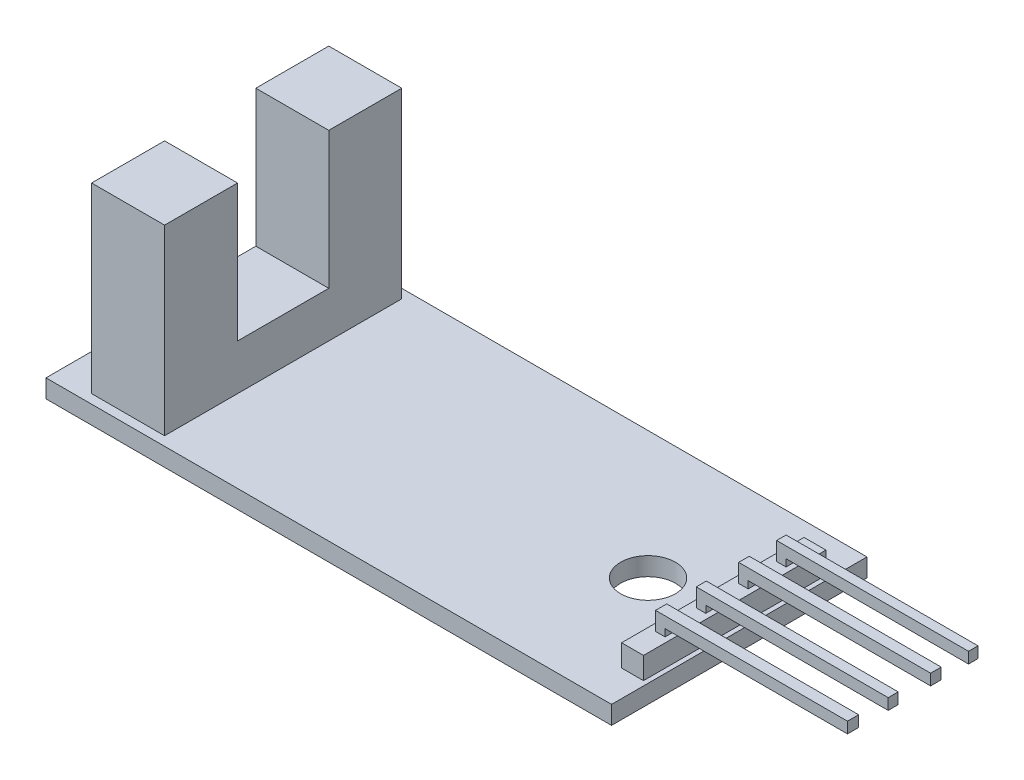
SolidWorks part; units mm, degrees
ref_plane "Front Plane" through (0, 0, 0) normal (0, 0, 1) x (1, 0, 0)
ref_plane "Top Plane" through (0, 0, 0) normal (0, 1, 0) x (1, 0, 0)
ref_plane "Right Plane" through (0, 0, 0) normal (1, 0, 0) x (0, 0, -1)
sketch "Sketch1" plane through (0, 0, 0) normal (0, 1, 0) x (1, 0, 0)
  line L1 (0, 0) -> (31, 0)
  line L2 (0, 0) -> (0, -14)
  line L3 (0, -14) -> (31, -14)
  line L4 (31, 0) -> (31, -14)
  dimension "D1" = 31
  dimension "D2" = 14
extrude "Boss-Extrude1" add sketch "Sketch1" along normal blind 1
sketch "Sketch2" plane through (0, 1, 0) normal (0, 1, 0) x (1, 0, 0)
  line L0 (0, -14) -> (31, -14) construction
  line L1 (2, -13.5) -> (6, -13.5)
  line L2 (2, -13.5) -> (2, -9.5)
  line L3 (2, -9.5) -> (6, -9.5)
  line L4 (6, -13.5) -> (6, -9.5)
  line L5 (2, -4.5) -> (6, -4.5)
  line L6 (2, -4.5) -> (2, -0.5)
  line L7 (2, -0.5) -> (6, -0.5)
  line L8 (6, -4.5) -> (6, -0.5)
  line L9 (0, 0) -> (0, -14) construction
  dimension "D1" = 5
  dimension "D2" = 4
  dimension "D3" = 4
  dimension "D4" = 0.5
  dimension "D5" = 4
  dimension "D6" = 4
  dimension "D7" = 2
  dimension "D8" = 2
extrude "Boss-Extrude2" add sketch "Sketch2" along normal blind 10
sketch "Sketch3" plane through (0, 1, 0) normal (0, 1, 0) x (1, 0, 0)
  line L0 (31, -14) -> (31, 0) construction
  circle A0 centre (26, -7) radius 1.5
  dimension "D1" = 3
  dimension "D2" = 5
extrude "Cut-Extrude1" cut sketch "Sketch3" against normal through all
sketch "Sketch4" plane through (0, 1, 0) normal (0, 1, 0) x (1, 0, 0)
  line L1 (2, -4.5) -> (6, -4.5)
  line L2 (2, -4.5) -> (2, -9.5)
  line L3 (2, -9.5) -> (6, -9.5)
  line L4 (6, -4.5) -> (6, -9.5)
extrude "Boss-Extrude3" add sketch "Sketch4" along normal blind 2.5
sketch "草图1" plane through (0, 1, 0) normal (0, 1, 0) x (1, 0, 0)
  line L0 (31, 0) -> (0, 0) construction
  line L1 (30.7509, -2) -> (29.5509, -2)
  line L2 (30.7509, -2) -> (30.7509, -12)
  line L3 (30.7509, -12) -> (29.5509, -12)
  line L4 (29.5509, -2) -> (29.5509, -12)
  line L5 (0, -14) -> (31, -14) construction
  dimension "D1" = 1.2
  dimension "D2" = 2
  dimension "D3" = 2
extrude "凸台-拉伸1" add sketch "草图1" along normal blind 1.2
sketch "草图2" plane through (0, 2.2, 0) normal (0, 1, 0) x (1, 0, 0)
  line L1 (29.9438, -3.3769) -> (30.4635, -3.3769)
  line L2 (29.9438, -3.3769) -> (29.9438, -3.8967)
  line L3 (29.9438, -3.8967) -> (30.4635, -3.8967)
  line L4 (30.4635, -3.3769) -> (30.4635, -3.8967)
  line L5 (29.9438, -5.3948) -> (30.4635, -5.3948)
  line L6 (29.9438, -5.3948) -> (29.9438, -5.9758)
  line L7 (29.9438, -5.9758) -> (30.4635, -5.9758)
  line L8 (30.4635, -5.3948) -> (30.4635, -5.9758)
  line L9 (29.9438, -7.7491) -> (30.4635, -7.7491)
  line L10 (29.9438, -7.7491) -> (29.9438, -8.2994)
  line L11 (29.9438, -8.2994) -> (30.4635, -8.2994)
  line L12 (30.4635, -7.7491) -> (30.4635, -8.2994)
  line L13 (29.9438, -9.9199) -> (30.4635, -9.9199)
  line L14 (29.9438, -9.9199) -> (29.9438, -10.5314)
  line L15 (29.9438, -10.5314) -> (30.4635, -10.5314)
  line L16 (30.4635, -9.9199) -> (30.4635, -10.5314)
extrude "凸台-拉伸2" add sketch "草图2" along normal blind 1
sketch "草图3" plane through (30.4635, 0, 0) normal (1, 0, 0) x (0, 0, -1)
  line L0 (-9.9199, 3.2) -> (-9.9199, 2.2) construction
  line L1 (-10.5314, 3.2) -> (-9.9199, 3.2)
  line L2 (-10.5314, 3.2) -> (-10.5314, 2.5931)
  line L3 (-10.5314, 2.5931) -> (-9.9199, 2.5931)
  line L4 (-9.9199, 3.2) -> (-9.9199, 2.5931)
  line L5 (-7.7491, 3.2) -> (-7.7491, 2.2) construction
  line L6 (-8.2994, 3.2) -> (-7.7491, 3.2)
  line L7 (-8.2994, 3.2) -> (-8.2994, 2.5931)
  line L8 (-8.2994, 2.5931) -> (-7.7491, 2.5931)
  line L9 (-7.7491, 3.2) -> (-7.7491, 2.5931)
  line L10 (-5.3948, 3.2) -> (-5.3948, 2.2) construction
  line L11 (-5.9758, 3.2) -> (-5.3948, 3.2)
  line L12 (-5.9758, 3.2) -> (-5.9758, 2.5931)
  line L13 (-5.9758, 2.5931) -> (-5.3948, 2.5931)
  line L14 (-5.3948, 3.2) -> (-5.3948, 2.5931)
  line L15 (-3.3769, 3.2) -> (-3.3769, 2.2) construction
  line L16 (-3.8967, 3.2) -> (-3.3769, 3.2)
  line L17 (-3.8967, 3.2) -> (-3.8967, 2.5931)
  line L18 (-3.8967, 2.5931) -> (-3.3769, 2.5931)
  line L19 (-3.3769, 3.2) -> (-3.3769, 2.5931)
extrude "凸台-拉伸3" add sketch "草图3" along normal blind 10
